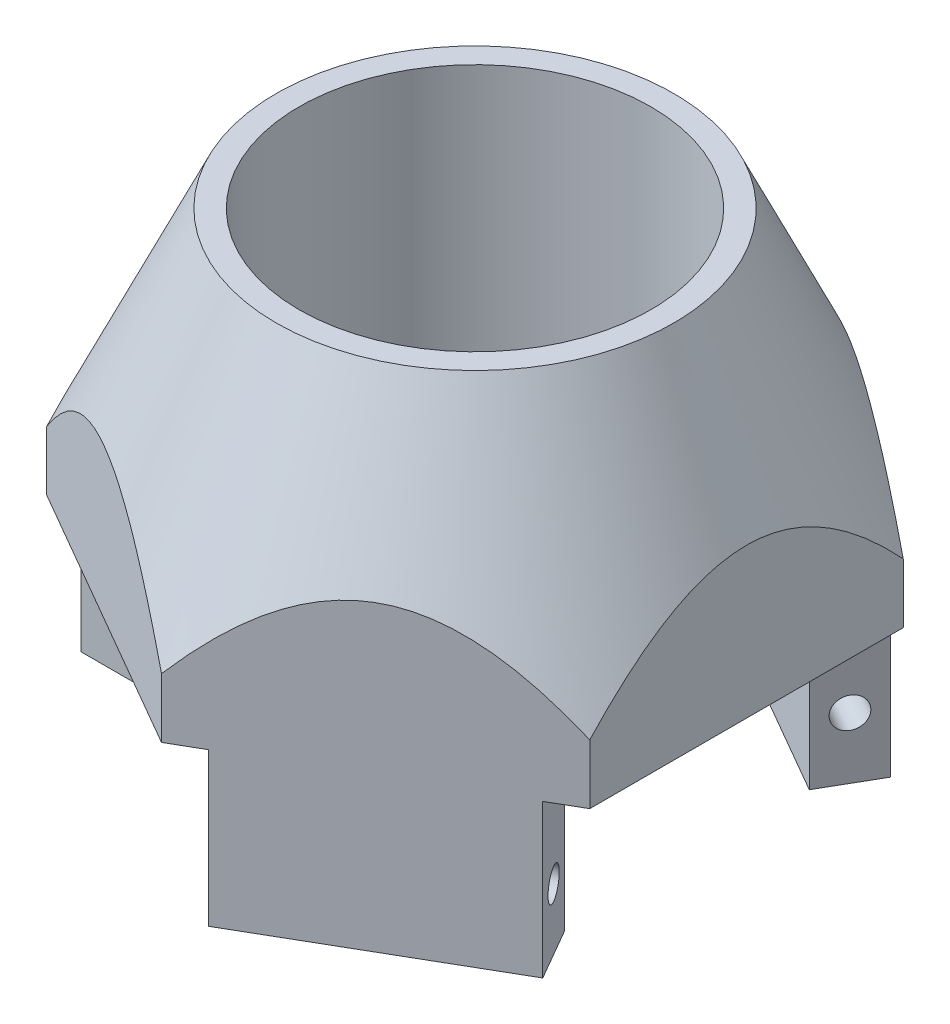
SolidWorks part; units mm, degrees
ref_plane "Front Plane" through (0, 0, 0) normal (0, 0, 1) x (1, 0, 0)
ref_plane "Top Plane" through (0, 0, 0) normal (0, 1, 0) x (1, 0, 0)
ref_plane "Right Plane" through (0, 0, 0) normal (1, 0, 0) x (0, 0, -1)
sketch "Sketch1" plane through (0, 0, 0) normal (0, 1, 0) x (1, 0, 0)
  line L1 (0, 20.5) -> (-17.7535, 10.25)
  line L2 (-17.7535, 10.25) -> (-17.7535, -10.25)
  line L3 (-17.7535, -10.25) -> (0, -20.5)
  line L4 (0, -20.5) -> (17.7535, -10.25)
  line L5 (17.7535, -10.25) -> (17.7535, 10.25)
  line L6 (17.7535, 10.25) -> (0, 20.5)
  circle A0 centre (0, 0) radius 11.5
  circle A2 centre (0, 0) radius 17.7535 construction
  dimension "D1" = 23
extrude "Boss-Extrude1" add sketch "Sketch1" along normal blind 30
sketch "Sketch2" plane through (0, 0, 0) normal (0, 0, 1) x (1, 0, 0)
  line L0 (0, 30) -> (0, 0) construction
  line L1 (20.5, 13.8974) -> (13, 30)
  line L2 (0, 30) -> (17.7535, 30) construction
  line L3 (13, 30) -> (0, 30)
  line L4 (0, 30) -> (0, 31.0978)
  line L5 (0, 31.0978) -> (25.3514, 31.0978)
  line L6 (25.3514, 31.0978) -> (24.9734, 13.8974)
  line L7 (24.9734, 13.8974) -> (20.5, 13.8974)
  dimension "D1" = 20.5
  dimension "D2" = 13
revolve "Cut-Revolve1" cut sketch "Sketch2" angle 360 about L0
sketch "Sketch4" plane through (0, 0, 0) normal (0, -1, 0) x (1, 0, 0)
  line L5 (-17.7535, -8) -> (-13.8564, -8)
  line L8 (-17.7535, -8) -> (-17.7535, 8)
  line L9 (-17.7535, 8) -> (-13.8564, 8)
  line L10 (-17.7535, -8) -> (-13.8564, -8)
  line L11 (-13.8564, 8) -> (-13.8564, -8)
  line L12 (1.9486, 19.375) -> (0, 16)
  line L13 (1.9486, 19.375) -> (15.805, 11.375)
  line L14 (15.805, 11.375) -> (13.8564, 8)
  line L15 (1.9486, 19.375) -> (0, 16)
  line L16 (13.8564, 8) -> (0, 16)
  line L17 (15.805, -11.375) -> (13.8564, -8)
  line L18 (15.805, -11.375) -> (1.9486, -19.375)
  line L19 (1.9486, -19.375) -> (0, -16)
  line L20 (15.805, -11.375) -> (13.8564, -8)
  line L21 (0, -16) -> (13.8564, -8)
  circle A0 centre (0, 0) radius 24.4023
  point P18 (-17.7535, 0)
  point P25 (0, 0)
  line M2 (0, -20.5) -> (17.7535, -10.25)
  line M3 (17.7535, -10.25) -> (17.7535, 10.25)
  line M4 (17.7535, 10.25) -> (0, 20.5)
  line M5 (0, 20.5) -> (-17.7535, 10.25)
  line M6 (-17.7535, 10.25) -> (-17.7535, -10.25)
  line M7 (-17.7535, -10.25) -> (0, -20.5)
  circle M8 centre (0, 0) radius 11.5
  dimension "D1" = 8
  dimension "D2" = 8
  dimension "D3" = 3
extrude "Cut-Extrude1" cut sketch "Sketch4" against normal blind 10 contours L19 L21 L17 L14 L16 L12 L9 L11 L5 M2 M3 M4 M5 M6 M7 M8
sketch "Sketch5" plane through (0, 0, 8) normal (0, 0, 1) x (1, 0, 0)
  line L0 (-17.7535, 0) -> (-13.8564, 0) construction
  circle A0 centre (-15.805, 4) radius 1
  point P5 (-15.805, 0)
  dimension "D1" = 2
  dimension "D2" = 4
extrude "Cut-Extrude2" cut sketch "Sketch5" against normal through all
sketch "Sketch6" plane through (-6.9282, 0, 4) normal (-0.866, 0, 0.5) x (0.5, 0, 0.866)
  line L0 (17.7535, 0) -> (13.8564, 0) construction
  circle A0 centre (15.805, 4) radius 1
  dimension "D1" = 2
  dimension "D2" = 4
extrude "Cut-Extrude3" cut sketch "Sketch6" against normal through all
sketch "Sketch7" plane through (6.9282, 0, 4) normal (0.866, 0, 0.5) x (0.5, 0, -0.866)
  line L0 (17.7535, 0) -> (13.8564, 0) construction
  circle A0 centre (15.805, 4) radius 1
  dimension "D1" = 2
  dimension "D2" = 4
extrude "Cut-Extrude4" cut sketch "Sketch7" against normal through all
